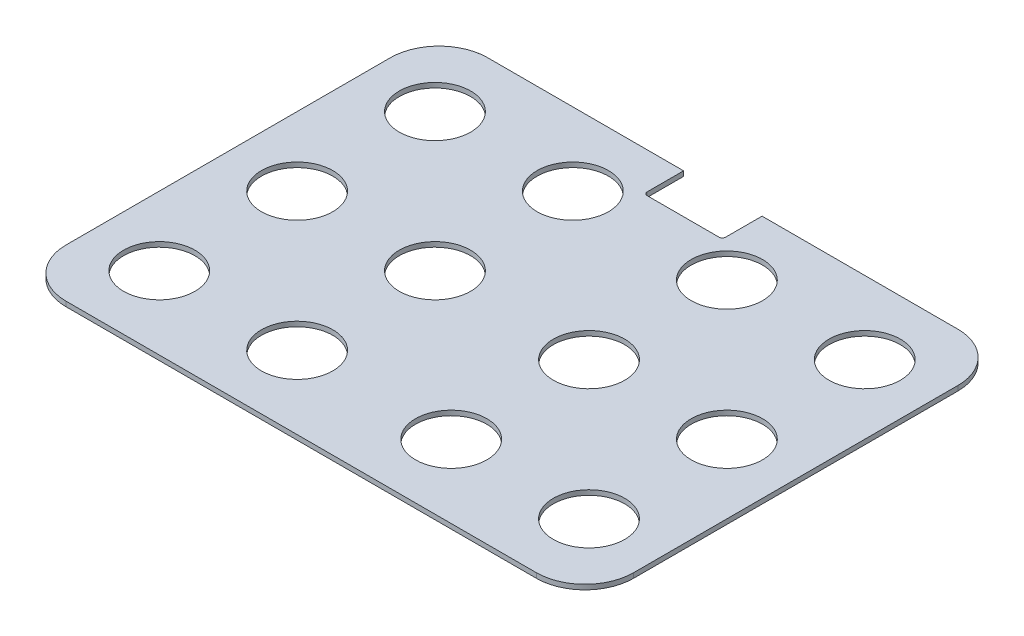
SolidWorks part; units mm, degrees
ref_plane "前基準面" through (0, 0, 0) normal (0, 0, 1) x (1, 0, 0)
ref_plane "上基準面" through (0, 0, 0) normal (0, 1, 0) x (1, 0, 0)
ref_plane "右基準面" through (0, 0, 0) normal (1, 0, 0) x (0, 0, -1)
sketch "草圖1" plane through (0, 0, 0) normal (0, 1, 0) x (1, 0, 0)
  line L1 (-175, -130) -> (175, -130)
  line L2 (-175, -130) -> (-175, 130)
  line L3 (-175, 130) -> (175, 130)
  line L4 (175, -130) -> (175, 130)
  line L5 (-175, -130) -> (175, 130) construction
  line L6 (-175, 130) -> (175, -130) construction
  point P0 (0, 0)
  dimension "D1" = 260
  dimension "D2" = 350
extrude "填料-伸長1" add sketch "草圖1" along normal blind 3
fillet "圓角2" radius 30 4 edges at (175, 1.5, -130) (175, 1.5, 130) (-175, 1.5, 130) (-175, 1.5, -130)
sketch "草圖3" plane through (0, 3, 0) normal (0, 1, 0) x (1, 0, 0)
  line L0 (-175, 100) -> (-175, -100) construction
  line L1 (145, 130) -> (-145, 130) construction
  circle A0 centre (-132.5, 85) radius 22
  dimension "D1" = 44
  dimension "D2" = 42.5
  dimension "D3" = 45
extrude "除料-伸長2" cut sketch "草圖3" against normal up to next
pattern_linear "直線複製排列1" count 2 spacing 85 along (1, 0, 0) count 3 spacing 85 along (0, 0, 1) of "除料-伸長2"
mirror "鏡射1" about plane through (0, 0, 0) normal (1, 0, 0) of "直線複製排列1", "除料-伸長2"
sketch "草圖4" plane through (0, 3, 0) normal (0, 1, 0) x (1, 0, 0)
  line L0 (145, 130) -> (-145, 130) construction
  line L1 (-24.2, 130) -> (24.2, 130)
  line L2 (-24.2, 130) -> (-24.2, 105.5)
  line L3 (-24.2, 105.5) -> (24.2, 105.5)
  line L4 (24.2, 130) -> (24.2, 105.5)
  line L5 (0, -1.65) -> (0, 1.65) construction
  dimension "D1" = 48.4
  dimension "D2" = 24.2
  dimension "D3" = 24.5
extrude "除料-伸長3" cut sketch "草圖4" against normal up to next
fillet "圓角3" radius 2 2 edges at (-24.2, 1.5, -105.5) (24.2, 1.5, -105.5)
